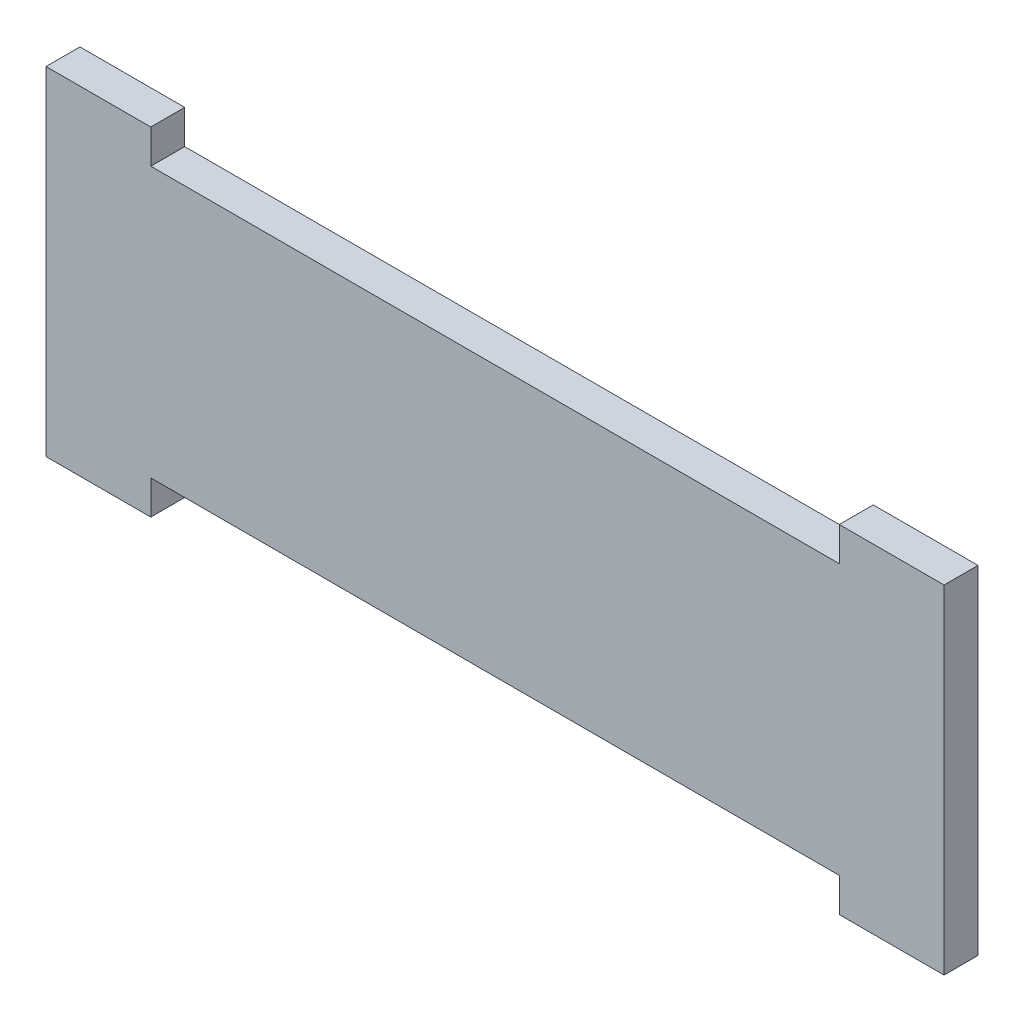
SolidWorks part; units mm, degrees
material "Acrylic (Medium-high impact)"
ref_plane "Front Plane" through (0, 0, 0) normal (0, 0, 1) x (1, 0, 0)
ref_plane "Top Plane" through (0, 0, 0) normal (0, 1, 0) x (1, 0, 0)
ref_plane "Right Plane" through (0, 0, 0) normal (1, 0, 0) x (0, 0, -1)
sketch "Sketch2" plane through (0, 0, 0) normal (0, 0, 1) x (1, 0, 0)
  line L0 (-46.1, 0) -> (-51, 0) construction
  line L1 (-51, 0) -> (-51, -1.5875) construction
  line L2 (-51, -1.5875) -> (-46.1, -1.5875) construction
  line L3 (-46.1, -1.5875) -> (-46.1, 0) construction
  line L4 (-9, 0) -> (-13.9, 0) construction
  line L5 (-13.9, 0) -> (-13.9, -1.5875) construction
  line L6 (-13.9, -1.5875) -> (-9, -1.5875) construction
  line L7 (-9, -1.5875) -> (-9, 0) construction
  line L8 (-46.1, 0) -> (-51, 0)
  line L9 (-51, 0) -> (-51, -1.5875)
  line L10 (-51, -1.5875) -> (-46.1, -1.5875)
  line L11 (-46.1, -1.5875) -> (-46.1, 0)
  line L12 (-9, 0) -> (-13.9, 0)
  line L13 (-13.9, 0) -> (-13.9, -1.5875)
  line L14 (-13.9, -1.5875) -> (-9, -1.5875)
  line L15 (-9, -1.5875) -> (-9, 0)
  line L16 (-51, -7.9) -> (-9, -7.9) construction
  line L17 (-9, -1.5875) -> (-51, -1.5875)
  line L18 (-9, -1.5875) -> (-9, -14.2125)
  line L19 (-9, -14.2125) -> (-51, -14.2125)
  line L20 (-51, -1.5875) -> (-51, -14.2125)
  line L21 (-9, -14.2125) -> (-9, -15.8)
  line L22 (-13.9, -14.2125) -> (-9, -14.2125)
  line L23 (-13.9, -15.8) -> (-13.9, -14.2125)
  line L24 (-9, -15.8) -> (-13.9, -15.8)
  line L25 (-46.1, -14.2125) -> (-46.1, -15.8)
  line L26 (-51, -14.2125) -> (-46.1, -14.2125)
  line L27 (-51, -15.8) -> (-51, -14.2125)
  line L28 (-46.1, -15.8) -> (-51, -15.8)
  dimension "D1" = 15.8
extrude "Boss-Extrude1" add sketch "Sketch2" along normal blind 1.5875 contours L16 L20 L19 L18 | L28 L25 L19 L27 | L20 L16 L18 L14 L17 L10 | L10 L11 L8 L9 | L14 L15 L12 L13 | L24 L21 L19 L23
